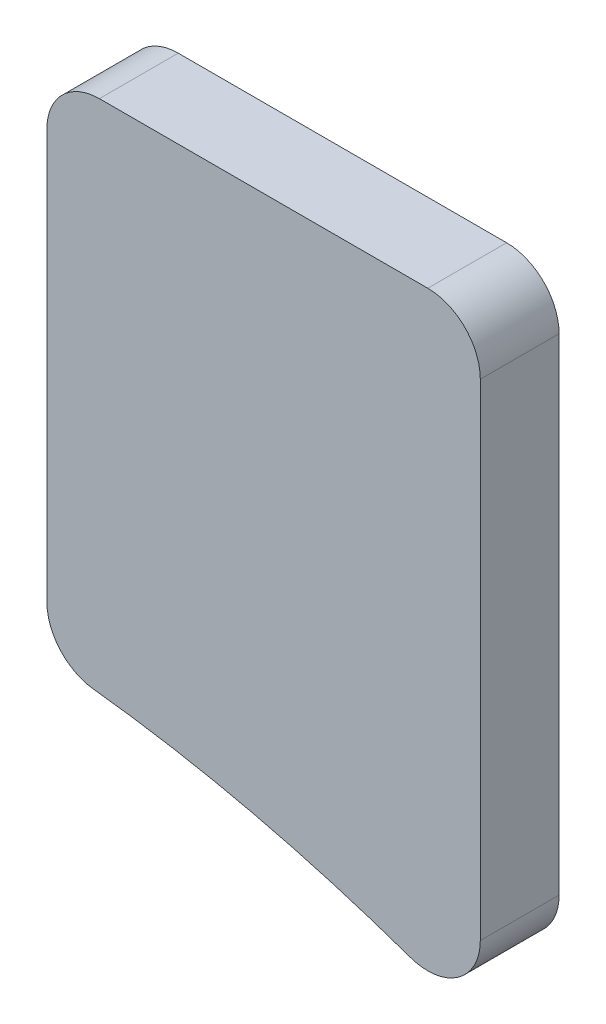
SolidWorks part; units mm, degrees
material "Natural Rubber"
ref_plane "Front Plane" through (0, 0, 0) normal (0, 0, 1) x (1, 0, 0)
ref_plane "Top Plane" through (0, 0, 0) normal (0, 1, 0) x (1, 0, 0)
ref_plane "Right Plane" through (0, 0, 0) normal (1, 0, 0) x (0, 0, -1)
sketch "Sketch2" plane through (0, 0, 0) normal (0, 0, 1) x (1, 0, 0)
  line L0 (0, 10.4576) -> (0, -13.7944) construction
  line L1 (-22.5, -13.7944) -> (22.5, -13.7944) construction
  line L2 (4, 10.4576) -> (4, -8.9524)
  line L3 (4, 10.4576) -> (20.5, 10.4576)
  line L4 (20.5, 10.4576) -> (20.5, -12.945)
  spline S0 degree 3 poles (4, -8.9524) (9.5, -9.387) (15, -10.7179) (20.5, -12.945) knots 0.588889 0.588889 0.588889 0.588889 0.955556 0.955556 0.955556 0.955556
  spline S1 degree 2 poles (-22.5, -13.7944) (-11.25, -8.7944) (0, -8.7944) knots 0 0 0 0.5 0.5 0.5 construction
  spline S2 degree 3 poles (0, -8.7944) (1.3333, -8.7944) (2.6667, -8.8471) (4, -8.9524) knots 0.5 0.5 0.5 0.5 0.588889 0.588889 0.588889 0.588889 construction
  spline S3 degree 2 poles (20.5, -12.945) (21.5, -13.35) (22.5, -13.7944) knots 0.955556 0.955556 0.955556 1 1 1 construction
  point P6 (0, -8.7944)
  dimension "D1" = 45
  dimension "D2" = 5
  dimension "D3" = 4
  dimension "D4" = 16.5
  dimension "D5" = 19.41
  dimension "D6" = 23.4026
extrude "Boss-Extrude1" add sketch "Sketch2" against normal blind 3
fillet "Fillet1" radius 2 4 edges at (20.5, -12.945, -1.5) (4, -8.9524, -1.5) (20.5, 10.4576, -1.5) (4, 10.4576, -1.5)
